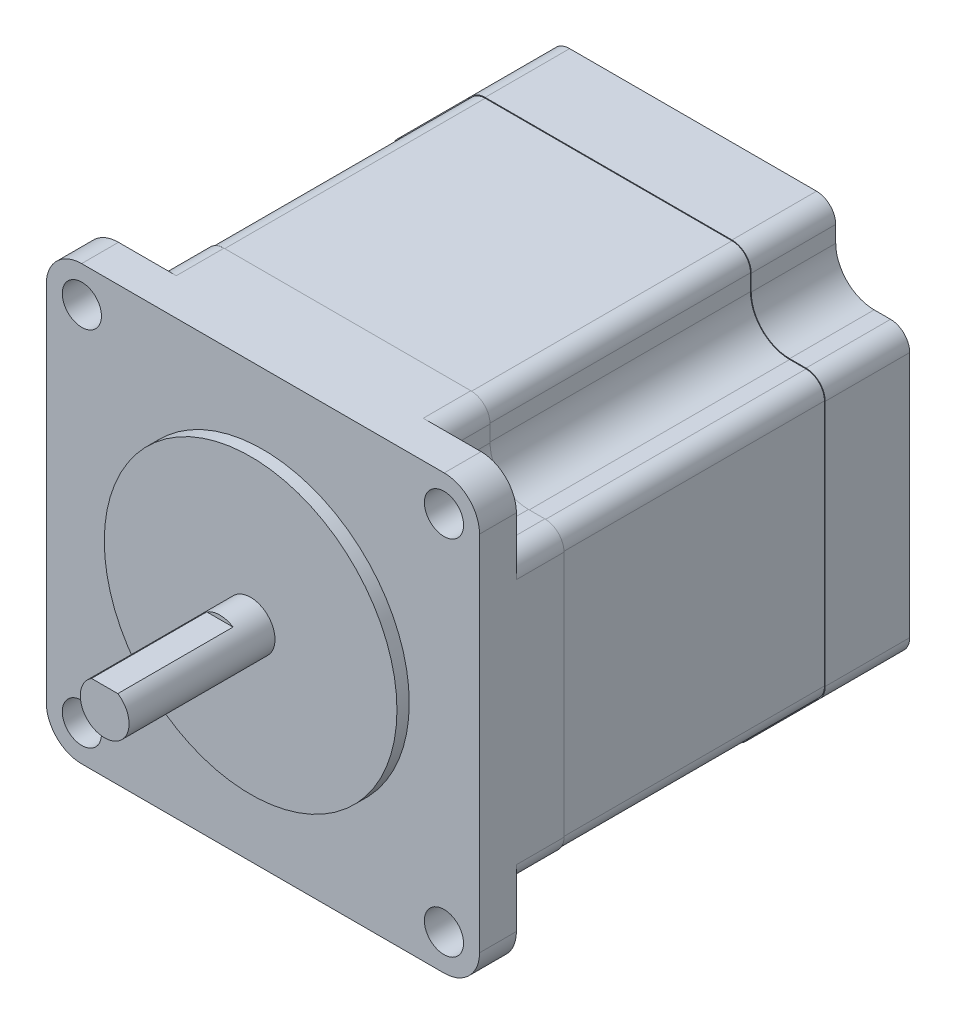
SolidWorks part; units mm, degrees
material "Plain Carbon Steel"
ref_plane "Front" through (0, 0, 0) normal (0, 0, 1) x (1, 0, 0)
ref_plane "Top" through (0, 0, 0) normal (0, 1, 0) x (1, 0, 0)
ref_plane "Right" through (0, 0, 0) normal (1, 0, 0) x (0, 0, -1)
sketch "Sketch1" plane through (0, 0, 0) normal (0, 0, 1) x (1, 0, 0)
  circle A0 centre (0, 0) radius 3.175
  dimension "D1" = 6.35
extrude "Boss-Extrude1" add sketch "Sketch1" along normal blind 20.6
sketch "Sketch2" plane through (0, 0, 0) normal (0, 0, -1) x (-1, 0, 0)
  circle A0 centre (0, 0) radius 19.05
  dimension "D1" = 38.1
extrude "Boss-Extrude2" add sketch "Sketch2" against normal blind 1.6
sketch "Sketch3" plane through (0, 0, 0) normal (0, 0, -1) x (-1, 0, 0)
  line L1 (23.6, -28.2) -> (-23.6, -28.2)
  line L2 (28.2, -23.6) -> (28.2, 23.6)
  line L3 (23.6, 28.2) -> (-23.6, 28.2)
  line L4 (-28.2, -23.6) -> (-28.2, 23.6)
  line L5 (28.2, -28.2) -> (-28.2, 28.2) construction
  line L6 (28.2, 28.2) -> (-28.2, -28.2) construction
  arc A0 (28.2, 23.6) -> (23.6, 28.2) centre (23.6, 23.6) ccw
  arc A1 (23.6, -28.2) -> (28.2, -23.6) centre (23.6, -23.6) ccw
  arc A2 (-23.6, -28.2) -> (-28.2, -23.6) centre (-23.6, -23.6) cw
  arc A3 (-23.6, 28.2) -> (-28.2, 23.6) centre (-23.6, 23.6) ccw
  point P0 (0, 0)
  dimension "D2" = 4.6
  dimension "D1" = 56.4
extrude "Boss-Extrude3" add sketch "Sketch3" along normal blind 4.8
sketch "Sketch4" plane through (0, 0, -4.8) normal (0, 0, -1) x (-1, 0, 0)
  line L0 (-12.9329, 0) -> (0, 0) construction
  line L1 (0, 0) -> (0, 12.5926) construction
  line L2 (-18.57, 23.57) -> (-18.57, 25.7)
  line L4 (28.2, 16.07) -> (28.2, -16.07)
  line L5 (-23.57, 18.57) -> (-25.7, 18.57)
  line L6 (16.07, 28.2) -> (-16.07, 28.2)
  line L7 (-28.2, 23.6) -> (-28.2, -23.6) construction
  line L8 (-28.2, 16.07) -> (-28.2, -16.07)
  line L9 (23.6, 28.2) -> (-23.6, 28.2) construction
  line L10 (23.57, 18.57) -> (25.7, 18.57)
  line L12 (18.57, 23.57) -> (18.57, 25.7)
  line L13 (18.57, -23.57) -> (18.57, -25.7)
  line L15 (23.57, -18.57) -> (25.7, -18.57)
  line L16 (16.07, -28.2) -> (-16.07, -28.2)
  line L17 (-23.57, -18.57) -> (-25.7, -18.57)
  line L19 (-18.57, -23.57) -> (-18.57, -25.7)
  arc A0 (-18.57, 25.7) -> (-16.07, 28.2) centre (-16.07, 25.7) cw
  arc A1 (-23.57, 18.57) -> (-18.57, 23.57) centre (-23.57, 23.57) ccw
  arc A2 (-25.7, 18.57) -> (-28.2, 16.07) centre (-25.7, 16.07) ccw
  arc A3 (25.7, 18.57) -> (28.2, 16.07) centre (25.7, 16.07) cw
  arc A4 (23.57, 18.57) -> (18.57, 23.57) centre (23.57, 23.57) cw
  arc A5 (18.57, 25.7) -> (16.07, 28.2) centre (16.07, 25.7) ccw
  arc A6 (18.57, -25.7) -> (16.07, -28.2) centre (16.07, -25.7) cw
  arc A7 (23.57, -18.57) -> (18.57, -23.57) centre (23.57, -23.57) ccw
  arc A8 (25.7, -18.57) -> (28.2, -16.07) centre (25.7, -16.07) ccw
  arc A9 (-25.7, -18.57) -> (-28.2, -16.07) centre (-25.7, -16.07) cw
  arc A10 (-23.57, -18.57) -> (-18.57, -23.57) centre (-23.57, -23.57) cw
  arc A11 (-18.57, -25.7) -> (-16.07, -28.2) centre (-16.07, -25.7) ccw
  point P16 (28.2, 0)
  point P27 (0, 28.2)
  point P49 (0, -28.2)
  point P51 (-28.2, 0)
  dimension "D2" = 47.14
  dimension "D3" = 2.5
  dimension "4.6*2" = 10
  dimension "D4" = 47.14
extrude "Boss-Extrude4" add sketch "Sketch4" along normal blind 51.2
sketch "Sketch7" plane through (0, 0, 20.6) normal (0, 0, 1) x (1, 0, 0)
  line L1 (-1.7103, 2.675) -> (1.7103, 2.675)
  line L2 (-1.7103, 2.675) -> (-1.7103, 3.7877)
  line L3 (-1.7103, 3.7877) -> (1.7103, 3.7877)
  line L4 (1.7103, 2.675) -> (1.7103, 3.7877)
  circle A0 centre (0, 0) radius 3.175 construction
  dimension "D1" = 5.85
extrude "Cut-Extrude5" cut sketch "Sketch7" against normal blind 15
sketch "Sketch8" plane through (0, 0, 0) normal (0, 0, 1) x (1, 0, 0)
  line L0 (-13.3219, 0) -> (0, 0) construction
  line L1 (0, 0) -> (0, 15.3153) construction
  circle A0 centre (-23.57, 23.57) radius 2.55
  circle A1 centre (23.57, 23.57) radius 2.55
  circle A2 centre (23.57, -23.57) radius 2.55
  circle A3 centre (-23.57, -23.57) radius 2.55
  circle A4 centre (0, 0) radius 3.175 construction
  dimension "D2" = 47.14
  dimension "D3" = 5.1
  dimension "D1" = 47.14
extrude "Cut-Extrude6" cut sketch "Sketch8" against normal up to next
ref_plane "Plane1" through (0, 0, -28) normal (0, 0, 1) x (1, 0, 0)
sketch "Sketch9" plane through (0, 0, -28) normal (0, 0, 1) x (1, 0, 0)
  line L24 (18.47, 23.57) -> (18.47, 25.7)
  line L25 (25.7, 18.47) -> (23.57, 18.47)
  line L26 (28.1, -16.07) -> (28.1, 16.07)
  line L27 (23.57, -18.47) -> (25.7, -18.47)
  line L28 (18.47, -25.7) -> (18.47, -23.57)
  line L29 (-16.07, -28.1) -> (16.07, -28.1)
  line L30 (-18.47, -23.57) -> (-18.47, -25.7)
  line L31 (-25.7, -18.47) -> (-23.57, -18.47)
  line L32 (-28.1, 16.07) -> (-28.1, -16.07)
  line L33 (-23.57, 18.47) -> (-25.7, 18.47)
  line L34 (-18.47, 25.7) -> (-18.47, 23.57)
  line L35 (16.07, 28.1) -> (-16.07, 28.1)
  line L36 (18.47, 23.57) -> (18.47, 25.7)
  line L37 (25.7, 18.47) -> (23.57, 18.47)
  line L38 (28.1, -16.07) -> (28.1, 16.07)
  line L39 (23.57, -18.47) -> (25.7, -18.47)
  line L40 (18.47, -25.7) -> (18.47, -23.57)
  line L41 (-16.07, -28.1) -> (16.07, -28.1)
  line L42 (-18.47, -23.57) -> (-18.47, -25.7)
  line L43 (-25.7, -18.47) -> (-23.57, -18.47)
  line L44 (-28.1, 16.07) -> (-28.1, -16.07)
  line L45 (-23.57, 18.47) -> (-25.7, 18.47)
  line L46 (-18.47, 25.7) -> (-18.47, 23.57)
  line L47 (16.07, 28.1) -> (-16.07, 28.1)
  line L48 (18.57, 23.57) -> (18.57, 25.7)
  line L49 (25.7, 18.57) -> (23.57, 18.57)
  line L50 (28.2, -16.07) -> (28.2, 16.07)
  line L51 (23.57, -18.57) -> (25.7, -18.57)
  line L52 (18.57, -25.7) -> (18.57, -23.57)
  line L53 (-16.07, -28.2) -> (16.07, -28.2)
  line L54 (-18.57, -23.57) -> (-18.57, -25.7)
  line L55 (-25.7, -18.57) -> (-23.57, -18.57)
  line L56 (-28.2, 16.07) -> (-28.2, -16.07)
  line L57 (-23.57, 18.57) -> (-25.7, 18.57)
  line L58 (-18.57, 25.7) -> (-18.57, 23.57)
  line L59 (16.07, 28.2) -> (-16.07, 28.2)
  line L60 (18.57, 23.57) -> (18.57, 25.7)
  line L61 (25.7, 18.57) -> (23.57, 18.57)
  line L62 (28.2, -16.07) -> (28.2, 16.07)
  line L63 (23.57, -18.57) -> (25.7, -18.57)
  line L64 (18.57, -25.7) -> (18.57, -23.57)
  line L65 (-16.07, -28.2) -> (16.07, -28.2)
  line L66 (-18.57, -23.57) -> (-18.57, -25.7)
  line L67 (-25.7, -18.57) -> (-23.57, -18.57)
  line L68 (-28.2, 16.07) -> (-28.2, -16.07)
  line L69 (-23.57, 18.57) -> (-25.7, 18.57)
  line L70 (-18.57, 25.7) -> (-18.57, 23.57)
  line L71 (16.07, 28.2) -> (-16.07, 28.2)
  arc A24 (18.47, 25.7) -> (16.07, 28.1) centre (16.07, 25.7) ccw
  arc A25 (18.47, 23.57) -> (23.57, 18.47) centre (23.57, 23.57) ccw
  arc A26 (28.1, 16.07) -> (25.7, 18.47) centre (25.7, 16.07) ccw
  arc A27 (25.7, -18.47) -> (28.1, -16.07) centre (25.7, -16.07) ccw
  arc A28 (23.57, -18.47) -> (18.47, -23.57) centre (23.57, -23.57) ccw
  arc A29 (16.07, -28.1) -> (18.47, -25.7) centre (16.07, -25.7) ccw
  arc A30 (-18.47, -25.7) -> (-16.07, -28.1) centre (-16.07, -25.7) ccw
  arc A31 (-18.47, -23.57) -> (-23.57, -18.47) centre (-23.57, -23.57) ccw
  arc A32 (-28.1, -16.07) -> (-25.7, -18.47) centre (-25.7, -16.07) ccw
  arc A33 (-25.7, 18.47) -> (-28.1, 16.07) centre (-25.7, 16.07) ccw
  arc A34 (-23.57, 18.47) -> (-18.47, 23.57) centre (-23.57, 23.57) ccw
  arc A35 (-16.07, 28.1) -> (-18.47, 25.7) centre (-16.07, 25.7) ccw
  arc A36 (18.47, 25.7) -> (16.07, 28.1) centre (16.07, 25.7) ccw
  arc A37 (18.47, 23.57) -> (23.57, 18.47) centre (23.57, 23.57) ccw
  arc A38 (28.1, 16.07) -> (25.7, 18.47) centre (25.7, 16.07) ccw
  arc A39 (25.7, -18.47) -> (28.1, -16.07) centre (25.7, -16.07) ccw
  arc A40 (23.57, -18.47) -> (18.47, -23.57) centre (23.57, -23.57) ccw
  arc A41 (16.07, -28.1) -> (18.47, -25.7) centre (16.07, -25.7) ccw
  arc A42 (-18.47, -25.7) -> (-16.07, -28.1) centre (-16.07, -25.7) ccw
  arc A43 (-18.47, -23.57) -> (-23.57, -18.47) centre (-23.57, -23.57) ccw
  arc A44 (-28.1, -16.07) -> (-25.7, -18.47) centre (-25.7, -16.07) ccw
  arc A45 (-25.7, 18.47) -> (-28.1, 16.07) centre (-25.7, 16.07) ccw
  arc A46 (-23.57, 18.47) -> (-18.47, 23.57) centre (-23.57, 23.57) ccw
  arc A47 (-16.07, 28.1) -> (-18.47, 25.7) centre (-16.07, 25.7) ccw
  arc A48 (18.57, 25.7) -> (16.07, 28.2) centre (16.07, 25.7) ccw
  arc A49 (18.57, 23.57) -> (23.57, 18.57) centre (23.57, 23.57) ccw
  arc A50 (28.2, 16.07) -> (25.7, 18.57) centre (25.7, 16.07) ccw
  arc A51 (25.7, -18.57) -> (28.2, -16.07) centre (25.7, -16.07) ccw
  arc A52 (23.57, -18.57) -> (18.57, -23.57) centre (23.57, -23.57) ccw
  arc A53 (16.07, -28.2) -> (18.57, -25.7) centre (16.07, -25.7) ccw
  arc A54 (-18.57, -25.7) -> (-16.07, -28.2) centre (-16.07, -25.7) ccw
  arc A55 (-18.57, -23.57) -> (-23.57, -18.57) centre (-23.57, -23.57) ccw
  arc A56 (-28.2, -16.07) -> (-25.7, -18.57) centre (-25.7, -16.07) ccw
  arc A57 (-25.7, 18.57) -> (-28.2, 16.07) centre (-25.7, 16.07) ccw
  arc A58 (-23.57, 18.57) -> (-18.57, 23.57) centre (-23.57, 23.57) ccw
  arc A59 (-16.07, 28.2) -> (-18.57, 25.7) centre (-16.07, 25.7) ccw
  arc A60 (18.57, 25.7) -> (16.07, 28.2) centre (16.07, 25.7) ccw
  arc A61 (18.57, 23.57) -> (23.57, 18.57) centre (23.57, 23.57) ccw
  arc A62 (28.2, 16.07) -> (25.7, 18.57) centre (25.7, 16.07) ccw
  arc A63 (25.7, -18.57) -> (28.2, -16.07) centre (25.7, -16.07) ccw
  arc A64 (23.57, -18.57) -> (18.57, -23.57) centre (23.57, -23.57) ccw
  arc A65 (16.07, -28.2) -> (18.57, -25.7) centre (16.07, -25.7) ccw
  arc A66 (-18.57, -25.7) -> (-16.07, -28.2) centre (-16.07, -25.7) ccw
  arc A67 (-18.57, -23.57) -> (-23.57, -18.57) centre (-23.57, -23.57) ccw
  arc A68 (-28.2, -16.07) -> (-25.7, -18.57) centre (-25.7, -16.07) ccw
  arc A69 (-25.7, 18.57) -> (-28.2, 16.07) centre (-25.7, 16.07) ccw
  arc A70 (-23.57, 18.57) -> (-18.57, 23.57) centre (-23.57, 23.57) ccw
  arc A71 (-16.07, 28.2) -> (-18.57, 25.7) centre (-16.07, 25.7) ccw
  dimension "D1" = 0.1
  dimension "D2" = 0
extrude "Cut-Extrude7" cut sketch "Sketch9" against normal mid plane 34
